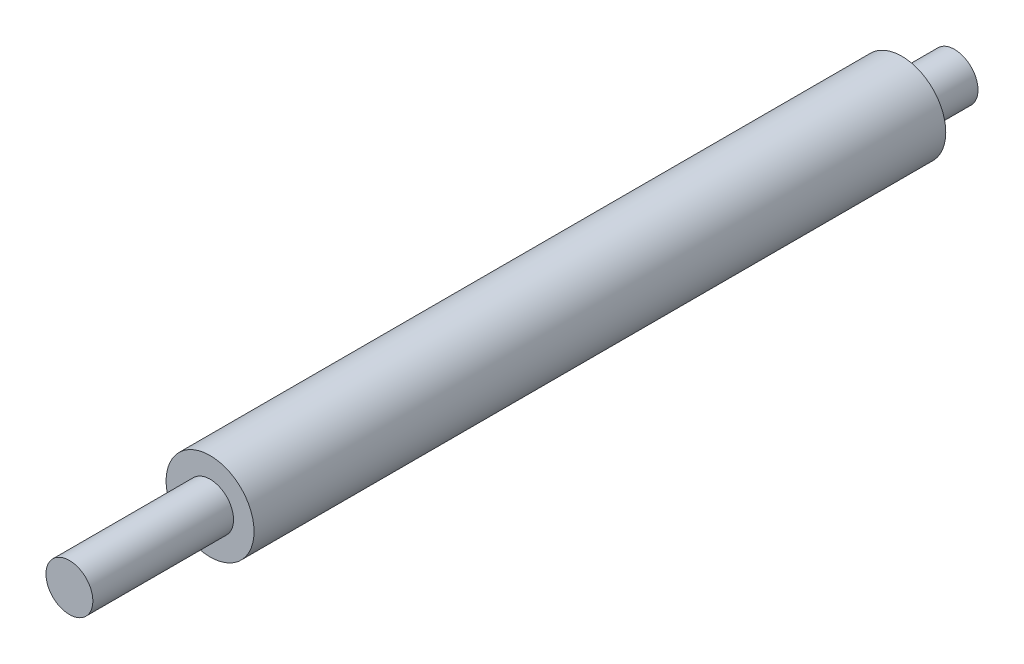
SolidWorks part; units mm, degrees
ref_plane "Front Plane" through (0, 0, 0) normal (0, 0, 1) x (1, 0, 0)
ref_plane "Top Plane" through (0, 0, 0) normal (0, 1, 0) x (1, 0, 0)
ref_plane "Right Plane" through (0, 0, 0) normal (1, 0, 0) x (0, 0, -1)
sketch "Sketch1" plane through (0, 0, 0) normal (0, 0, 1) x (1, 0, 0)
  circle A0 centre (0, 0) radius 37.5
  dimension "D1" = 75
extrude "Boss-Extrude1" add sketch "Sketch1" along normal mid plane 590
sketch "Sketch2" plane through (0, 0, 295) normal (0, 0, 1) x (1, 0, 0)
  circle A0 centre (0, 0) radius 20
  dimension "D1" = 40
extrude "Boss-Extrude2" add sketch "Sketch2" along normal blind 120
sketch "Sketch3" plane through (0, 0, -295) normal (0, 0, -1) x (-1, 0, 0)
  circle A0 centre (0, 0) radius 20
  dimension "D1" = 40
extrude "Boss-Extrude3" add sketch "Sketch3" along normal blind 45
